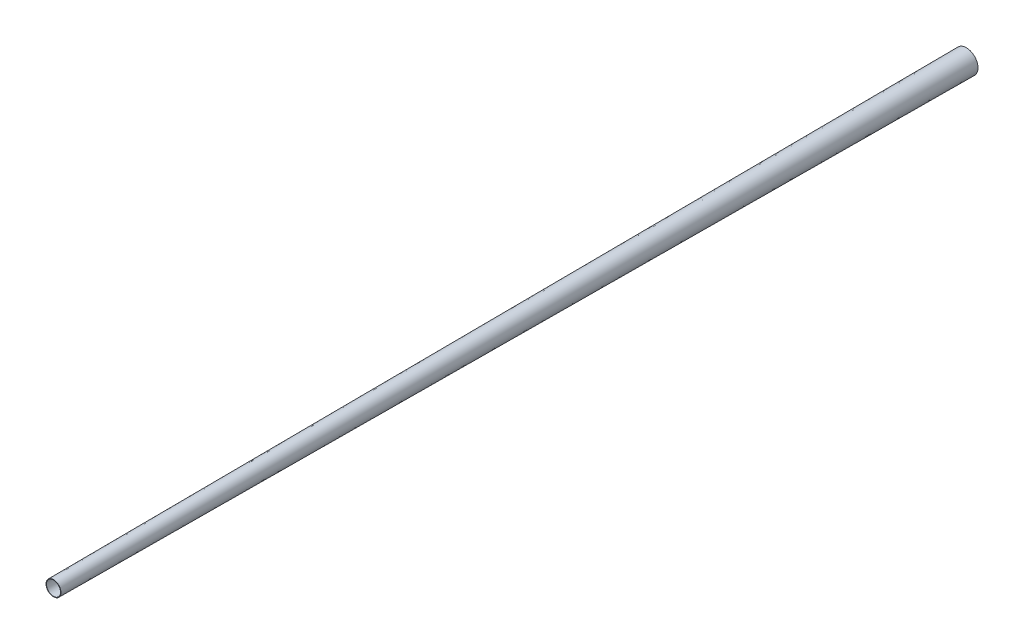
SolidWorks part; units mm, degrees
ref_plane "Front Plane" through (0, 0, 0) normal (0, 0, 1) x (1, 0, 0)
ref_plane "Top Plane" through (0, 0, 0) normal (0, 1, 0) x (1, 0, 0)
ref_plane "Right Plane" through (0, 0, 0) normal (1, 0, 0) x (0, 0, -1)
sketch "Sketch1" plane through (0, 0, 0) normal (0, 0, 1) x (1, 0, 0)
  circle A0 centre (0, 0) radius 13.2715
  circle A1 centre (0, 0) radius 12.7
ref_plane "Plane2" through (0, 0, 1035.05) normal (0, 0, 1) x (1, 0, 0)
sketch "Sketch3" plane through (0, 0, 1035.05) normal (0, 0, 1) x (1, 0, 0)
  circle A0 centre (0, 0) radius 8.4836
  circle A1 centre (0, 0) radius 7.9883
loft "Loft1" add section "Sketch3" section "Sketch1"
shell "Shell1" thickness 0.508
